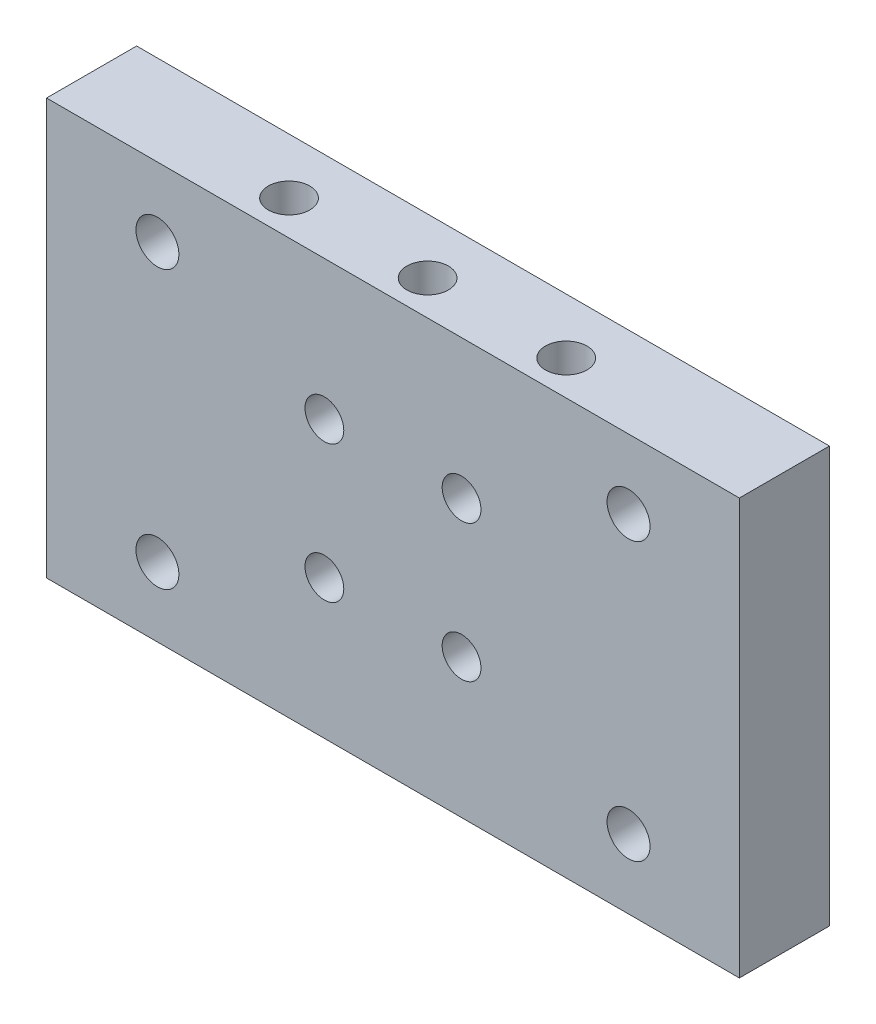
SolidWorks part; units mm, degrees
ref_plane "前视基准面" through (0, 0, 0) normal (0, 0, 1) x (1, 0, 0)
ref_plane "上视基准面" through (0, 0, 0) normal (0, 1, 0) x (1, 0, 0)
ref_plane "右视基准面" through (0, 0, 0) normal (1, 0, 0) x (0, 0, -1)
sketch "草图1" plane through (0, 0, 0) normal (0, 0, 1) x (1, 0, 0)
  line L1 (25, -15) -> (-25, -15)
  line L2 (25, -15) -> (25, 15)
  line L3 (25, 15) -> (-25, 15)
  line L4 (-25, -15) -> (-25, 15)
  line L5 (25, -15) -> (-25, 15) construction
  line L6 (25, 15) -> (-25, -15) construction
  point P0 (0, 0)
  dimension "D1" = 30
  dimension "D2" = 50
extrude "凸台-拉伸1" add sketch "草图1" along normal blind 6.5
sketch "草图2" plane through (0, 0, 6.5) normal (0, 0, 1) x (1, 0, 0)
  line L1 (4.95, -4.95) -> (-4.95, -4.95)
  line L2 (4.95, -4.95) -> (4.95, 4.95)
  line L3 (4.95, 4.95) -> (-4.95, 4.95)
  line L4 (-4.95, -4.95) -> (-4.95, 4.95)
  line L5 (4.95, -4.95) -> (-4.95, 4.95) construction
  line L6 (4.95, 4.95) -> (-4.95, -4.95) construction
  circle A0 centre (4.95, 4.95) radius 1.4
  circle A1 centre (-4.95, 4.95) radius 1.4
  circle A2 centre (-4.95, -4.95) radius 1.4
  circle A3 centre (4.95, -4.95) radius 1.4
  point P0 (0, 0)
  dimension "D1" = 9.9
  dimension "D3" = 2.8
  dimension "D2" = 9.9
extrude "切除-拉伸1" cut sketch "草图2" against normal through all contours L3 A1 L4 | L4 A1 L3 | L3 A0 L2 | L2 A0 L3 | L1 A3 L2 | L2 A3 L1 | L4 A2 L1 | L1 A2 L4
sketch "草图4" plane through (0, 0, 0) normal (0, 0, -1) x (-1, 0, 0)
  line L0 (-25, 0) -> (-17, 0) construction
  line L1 (-25, -15) -> (-25, 15) construction
  line L2 (-17, 0) -> (-17, 10) construction
  line L3 (0, 0) -> (0, -15) construction
  line L4 (25, -15) -> (-25, -15) construction
  line L5 (17, 0) -> (17, 10) construction
  circle A0 centre (-17, 10) radius 1.55
  circle A1 centre (-17, -10) radius 1.55
  circle A2 centre (17, -10) radius 1.55
  circle A3 centre (17, 10) radius 1.55
  dimension "D1" = 3.1
  dimension "D2" = 10
  dimension "D3" = 8
extrude "切除-拉伸2" cut sketch "草图4" against normal through all
sketch "草图5" plane through (0, 15, 0) normal (0, 1, 0) x (1, 0, 0)
  circle A0 centre (-10, -4) radius 1.5
  circle A1 centre (0, -4) radius 1.5
  circle A2 centre (10, -4) radius 1.5
extrude "切除-拉伸3" cut sketch "草图5" against normal through all
